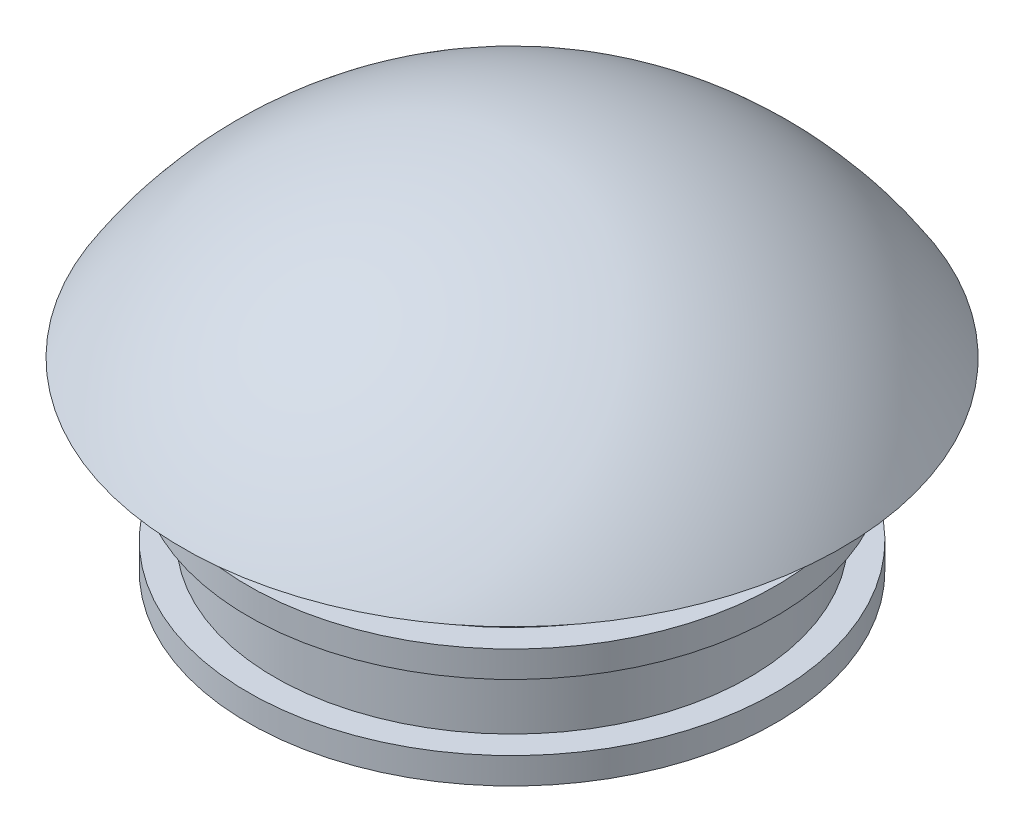
SolidWorks part; units mm, degrees
ref_plane "Спереди" through (0, 0, 0) normal (0, 0, 1) x (1, 0, 0)
ref_plane "Сверху" through (0, 0, 0) normal (0, 1, 0) x (1, 0, 0)
ref_plane "Справа" through (0, 0, 0) normal (1, 0, 0) x (0, 0, -1)
sketch "Эскиз1" plane through (0, 0, 0) normal (0, 0, 1) x (1, 0, 0)
  line L0 (-8, 4) -> (-8, -3)
  line L1 (-8, -3) -> (-10, -3)
  line L2 (-9, -2) -> (-9, 0.5)
  line L3 (-9, 4) -> (-12.5, 4)
  line L4 (-9, 1.5) -> (-10, 1.5)
  line L5 (-10, 1.5) -> (-10, 0.5)
  line L6 (-10, 0.5) -> (-9, 0.5)
  line L7 (-10, -3) -> (-10, -2)
  line L8 (-10, -2) -> (-9, -2)
  line L9 (-8, 4) -> (0, 4)
  line L10 (0, 4) -> (0, 11)
  line L11 (-9, 1.5) -> (-9, 4)
  arc A0 (-12.5, 4) -> (0, 11) centre (0.1893, -3.9988) cw
  dimension "D1" = 7
  dimension "D12" = 15
  dimension "D2" = 1
  dimension "D3" = 1
  dimension "D4" = 1
  dimension "D5" = 10
  dimension "D6" = 12.5
  dimension "D7" = 7
  dimension "D8" = 7
  dimension "D9" = 1
  dimension "D10" = 1
  dimension "D11" = 3.5
  dimension "D13" = 3
revolve "Повернуть1" add sketch "Эскиз1" angle 360 about L10
